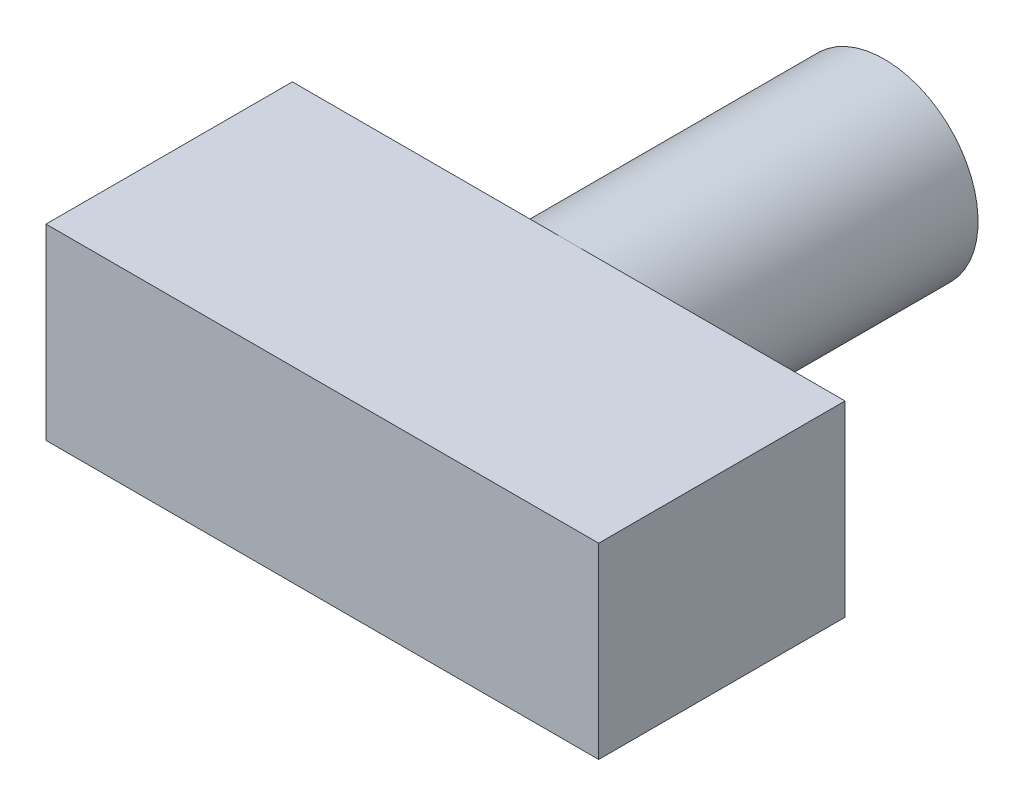
SolidWorks part; units mm, degrees
ref_plane "Plano frontal" through (0, 0, 0) normal (0, 0, 1) x (1, 0, 0)
ref_plane "Plano superior" through (0, 0, 0) normal (0, 1, 0) x (1, 0, 0)
ref_plane "Plano direito" through (0, 0, 0) normal (1, 0, 0) x (0, 0, -1)
sketch "Esboço4" plane through (0, 0, 6.74) normal (0, 0, 1) x (1, 0, 0)
  line L1 (64.2448, -35.3219) -> (76.0448, -35.3219)
  line L2 (64.2448, -35.3219) -> (64.2448, -39.3219)
  line L3 (64.2448, -39.3219) -> (76.0448, -39.3219)
  line L4 (76.0448, -35.3219) -> (76.0448, -39.3219)
  line L5 (64.2448, -35.3219) -> (76.0448, -39.3219) construction
  line L6 (64.2448, -39.3219) -> (76.0448, -35.3219) construction
  point P8 (70.1448, -37.3219)
  dimension "D1" = 11.8
  dimension "D4" = 4
extrude "Ressalto-extrusão2" add sketch "Esboço4" along normal blind 5.26
sketch "Esboço5" plane through (0, 0, 6.74) normal (0, 0, -1) x (-1, 0, 0)
  line L0 (-76.0448, -39.3219) -> (-76.0448, -35.3219) construction
  line L1 (-76.0448, -35.3219) -> (-64.2448, -35.3219) construction
  circle A0 centre (-70.1448, -37.3219) radius 2
  dimension "D2" = 4
  dimension "D1" = 5.9
  dimension "D3" = 2
extrude "Ressalto-extrusão4" add sketch "Esboço5" along normal blind 6.74
